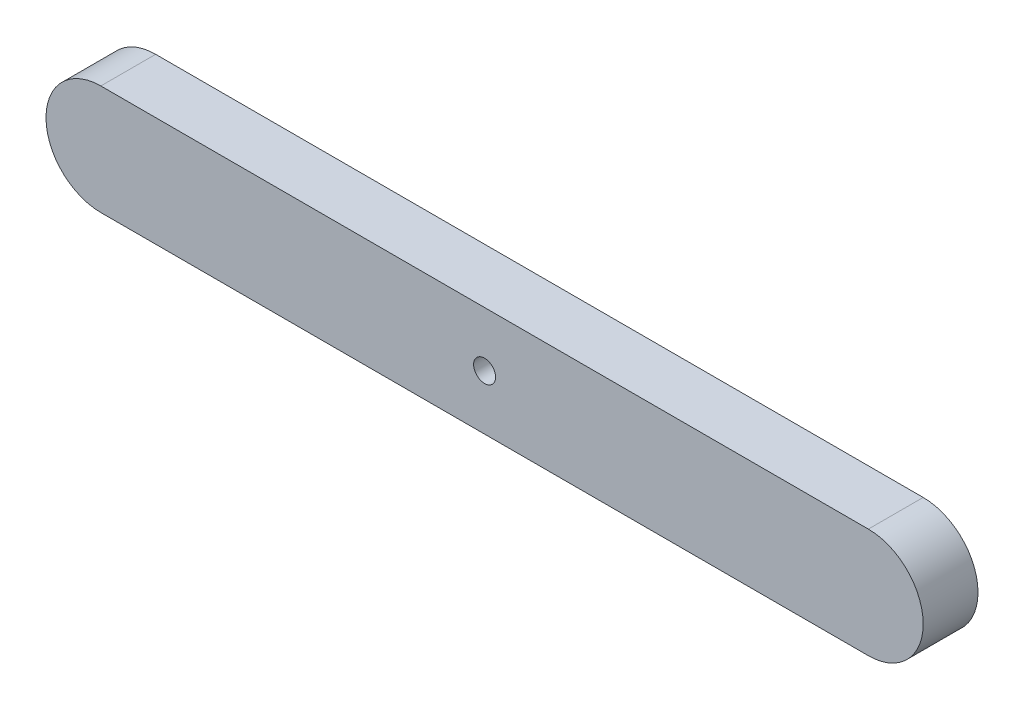
SolidWorks part; units mm, degrees
ref_plane "Alzado" through (0, 0, 0) normal (0, 0, 1) x (1, 0, 0)
ref_plane "Planta" through (0, 0, 0) normal (0, 1, 0) x (1, 0, 0)
ref_plane "Vista lateral" through (0, 0, 0) normal (1, 0, 0) x (0, 0, -1)
sketch "Croquis1" plane through (0, 0, 0) normal (0, 0, 1) x (1, 0, 0)
  line L1 (-35, 5) -> (35, 5)
  line L3 (-35, -5) -> (35, -5)
  arc A0 (-35, 5) -> (-35, -5) centre (-35, 0) ccw
  arc A1 (35, -5) -> (35, 5) centre (35, 0) ccw
  point P0 (0, 0)
extrude "Saliente-Extruir2" add sketch "Croquis1" along normal blind 5
sketch "Croquis2" plane through (0, 0, 0) normal (0, 0, -1) x (-1, 0, 0)
  circle A0 centre (0, 0) radius 1
extrude "Cortar-Extruir1" cut sketch "Croquis2" against normal blind 10
